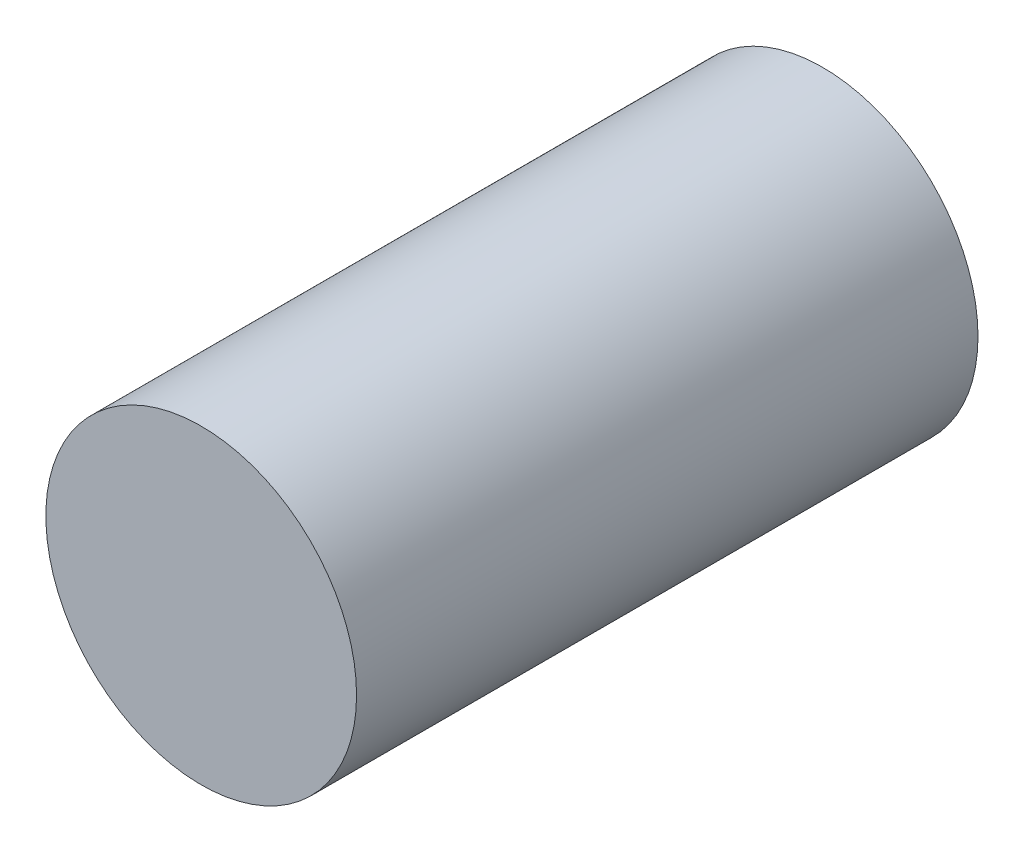
SolidWorks part; units mm, degrees
material "Nikel"
ref_plane "Ön Düzlem" through (0, 0, 0) normal (0, 0, 1) x (1, 0, 0)
ref_plane "Üst Düzlem" through (0, 0, 0) normal (0, 1, 0) x (1, 0, 0)
ref_plane "Sağ Düzlem" through (0, 0, 0) normal (1, 0, 0) x (0, 0, -1)
sketch "Çizim1" plane through (0, 0, 0) normal (0, 0, 1) x (1, 0, 0)
  circle A0 centre (0, 0) radius 0.25
extrude "Yükseklik-Ekstrüzyon1" add sketch "Çizim1" along normal blind 1
